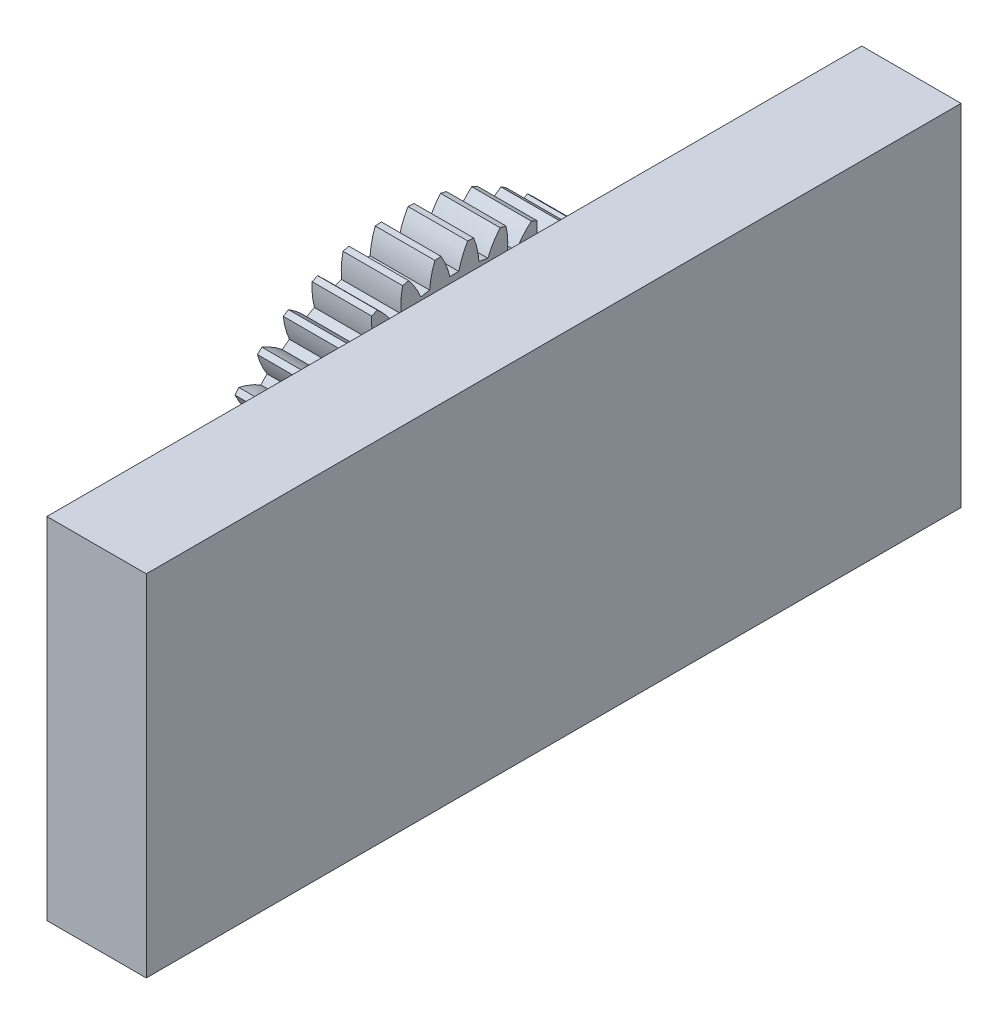
SolidWorks part; units mm, degrees
ref_plane "Plane1" through (0, 0, 0) normal (0, 0, 1) x (1, 0, 0)
ref_plane "Plane2" through (0, 0, 0) normal (0, 1, 0) x (1, 0, 0)
ref_plane "Plane3" through (0, 0, 0) normal (1, 0, 0) x (0, 0, -1)
other "Configuration Table"
sketch "HoldingSke" plane through (0, 0, 0) normal (0, 1, 0) x (1, 0, 0)
  line L0 (0, 0) -> (0.7771, -0.6293)
  line L1 (-15, 0) -> (100, 0) construction
  line L2 (0, 0) -> (-2.1039, 2.3779)
  line L3 (0, 0) -> (-11.863, 4.5341)
  line L4 (0, 0) -> (6.7114, 5.4348)
  line L5 (0, 0) -> (-46.8476, -17.4728)
  line L6 (0, 0) -> (-4.9738, -3.3558)
  line L7 (-2.1039, 2.3779) -> (8.6586, 51.2059)
  line L8 (-76.2, 54.61) -> (-72.9, 54.61)
  line L9 (-71.009, 38.7566) -> (-53.1078, 45.2721)
  line L10 (-76.2, 71.12) -> (104.1128, 71.12)
  line L11 (0, 0) -> (-6, 0)
  line L12 (-76.2, 101.6) -> (-76.162, 101.6)
  line L13 (24.9733, 27.94) -> (52.9518, 28.4284)
  line L14 (24.9733, 27.94) -> (24.9743, 27.94)
  line L15 (24.9733, 27.94) -> (100.4006, 29.5858)
  line L16 (-63.627, -1) -> (-12.827, -1)
  circle A0 centre (0, 0) radius 11
  circle A1 centre (0, 0) radius 18.249
  circle A2 centre (0, 0) radius 37.5
  circle A3 centre (0, 0) radius 11
  dimension "MHD" = 36.498
  dimension "Hub_dia" = 75
  dimension "Bore" = 22
  dimension "MBD" = 22
  dimension "Num_teeth" = 39
  dimension "Pitch" = 1
  dimension "Overall_len" = 50
  dimension "Show_teeth" = 39
  dimension "Thickness" = 6
  dimension "OAL" = 50.0001
  dimension "T_dim" = 3.3
  dimension "Ap" = 20
  dimension "H" = 19.05
  dimension "Pitch_radius" = 180.3128
  dimension "Width" = 6
  dimension "Backlash" = 0.038
  dimension "Addendum_fac" = 1
  dimension "Dedendum_fac" = 1.25
  dimension "Clearance_fac" = 0.25
  dimension "Dedendum_add" = 0.001
  dimension "Module" = 1
sketch "BasProSke" plane through (0, 0, 0) normal (0, 1, 0) x (1, 0, 0)
  line L0 (-10, 0) -> (60, 0) construction
  line L1 (0, 0) -> (0, 20.5)
  line L2 (0, 0) -> (6, 0)
  line L3 (6, 0) -> (6, 20.5)
  line L4 (6, 20.5) -> (0, 20.5)
  dimension "Thickness" = 6
  dimension "Diameter" = 41
revolve "Base-Revolve" add sketch "BasProSke" angle 360 about L0
sketch "TooCutSke" plane through (0, 0, 0) normal (1, 0, 0) x (0, 0, -1)
  line L1 (0, 0) -> (0, 107) construction
  line L2 (0, 0) -> (-0.8517, 19.4814) construction
  line L3 (0, 0) -> (-3.1361, 38.8471) construction
  line L4 (-0.8517, 19.4814) -> (-1.568, 19.4236) construction
  arc A0 (0.4501, 18.2434) -> (-0.4501, 18.2434) centre (0, 0) ccw
  arc A1 (1.358, 20.4804) -> (-1.358, 20.4804) centre (0, 0) ccw
  circle A2 centre (0, 0) radius 19.5 construction
  circle A3 centre (0, 0) radius 18.324 construction
  arc A4 (-0.4501, 18.2434) -> (-1.358, 20.4804) centre (-8.0443, 16.4638) ccw
  arc A5 (1.358, 20.4804) -> (0.4501, 18.2434) centre (8.0443, 16.4638) ccw
  dimension "Root_dia" = 36.498
  dimension "Overcut_dia" = 41.0508
  dimension "Pitch_dia" = 39
  dimension "Base_dia" = 36.648
  dimension "Flank_rad" = 7.8
  dimension "Half_ang" = 4.615
  dimension "Half_CT" = 0.7187
extrude "ToothCut" cut sketch "TooCutSke" along normal through all
fillet "Breaks" [suppressed] radius 0.02
fillet "RootFillets" [suppressed] radius 0.251
pattern_circular "TeethCuts" count 39 every 9.231 about axis through (-10, 0, 0) along (1, 0, 0) of "ToothCut", "RootFillets", "Breaks"
sketch "HubNeaOneSke" plane through (0, 0, 0) normal (-1, 0, 0) x (0, 0, 1)
  circle A0 centre (0, 0) radius 18.249
  dimension "Diameter" = 36.498
extrude "HubNearOne" [suppressed] add sketch "HubNeaOneSke" along normal blind 44.0001
sketch "HubNeaBotSke" plane through (0, 0, 0) normal (-1, 0, 0) x (0, 0, 1)
  circle A0 centre (0, 0) radius 18.249
  dimension "Diameter" = 36.498
extrude "HubNearBoth" [suppressed] add sketch "HubNeaBotSke" along normal blind 22
ref_plane "FarPln" through (6, 0, 0) normal (1, 0, 0) x (0, 0, -1)
sketch "HubFarSke" plane through (6, 0, 0) normal (1, 0, 0) x (0, 0, -1)
  circle A0 centre (0, 0) radius 18.249
  dimension "Diameter" = 36.498
extrude "HubFar" [suppressed] add sketch "HubFarSke" along normal blind 22
sketch "BorSke" plane through (0, 0, 0) normal (1, 0, 0) x (0, 0, -1)
  circle A0 centre (0, 0) radius 11
  dimension "Diameter" = 22
extrude "Bore" cut sketch "BorSke" along normal mid plane 100.0001
sketch "KeySke" plane through (0, 0, 0) normal (1, 0, 0) x (0, 0, -1)
  line L0 (-4, 0) -> (-4, 14.3)
  line L1 (-4, 14.3) -> (4, 14.3)
  line L2 (4, 14.3) -> (4, 0)
  line L3 (0, 0) -> (0, 34) construction
  line L4 (-4, 0) -> (4, 0)
  dimension "Offset" = 14.3
  dimension "Width" = 8
extrude "Keyway" [suppressed] cut sketch "KeySke" along normal mid plane 100.0001
pattern_circular "Keyway2" [suppressed] count 2 every 90 about axis through (-10, 0, 0) along (1, 0, 0)
sketch "Sketch1" plane through (6, 0, 0) normal (1, 0, 0) x (0, 0, -1)
  line L1 (-41.0054, -17.6156) -> (41.0054, -17.6156)
  line L2 (-41.0054, -17.6156) -> (-41.0054, 17.6156)
  line L3 (-41.0054, 17.6156) -> (41.0054, 17.6156)
  line L4 (41.0054, -17.6156) -> (41.0054, 17.6156)
  line L5 (-41.0054, -17.6156) -> (41.0054, 17.6156) construction
  line L6 (-41.0054, 17.6156) -> (41.0054, -17.6156) construction
  point P0 (0, 0)
extrude "Boss-Extrude1" add sketch "Sketch1" along normal blind 10
equation "' \"Module@HoldingSke\" = 6.35"
equation "' \"Num_teeth@HoldingSke\" = 12"
equation "' \"Ap@HoldingSke\" =  20"
equation "' \"Ap@HoldingSke\" = 20"
equation "' \"Width@HoldingSke\" = 0.5 * 25.4"
equation "' \"Hub_dia@HoldingSke\"= 1 * 25.4"
equation "' \"Hub_dia@HoldingSke\" = 1 * 25.4"
equation "' \"Overall_len@HoldingSke\" = 1.0 * 25.4"
equation "' \"Bore@HoldingSke\" = 0.75 * 25.4"
equation "' \"T_dim@HoldingSke\" = 0.1 * 25.4"
equation "' \"Width@KeySke\" = 0.25 * 25.4"
equation "' \"Show_teeth@HoldingSke\" = 13"
equation "' \"Backlash@HoldingSke\" = 0.009 * 25.4"
equation "' \"Addendum_fac@HoldingSke\" = 1.0"
equation "' \"Dedendum_fac@HoldingSke\" = 1.25"
equation "' \"Dedendum_add@HoldingSke\" = 0.00005 * 25.4"
equation "' \"Clearance_fac@HoldingSke\" = 0.25"
equation "\"Pitch@HoldingSke\" = 1 / \"Module@HoldingSke\""
equation "\"Overcut_dia@TooCutSke\" = (\"Num_teeth@HoldingSke\" + 2 * \"Addendum_fac@HoldingSke\") / \"Pitch@HoldingSke\" + 0.002 * 25.4"
equation "\"Pitch_dia@TooCutSke\" = \"Num_teeth@HoldingSke\" / \"Pitch@HoldingSke\""
equation "\"Base_dia@TooCutSke\" = \"Num_teeth@HoldingSke\" / \"Pitch@HoldingSke\" * cos((\"Ap@HoldingSke\"  * 3.14159265 / 180))"
equation "\"Root_dia@TooCutSke\" = (\"Num_teeth@HoldingSke\" + 2) / \"Pitch@HoldingSke\" - 2 * (\"Addendum_fac@HoldingSke\" + \"Dedendum_fac@HoldingSke\") / \"Pitch@HoldingSke\" - \"Dedendum_add@HoldingSke\" * 2"
equation "\"Half_ang@TooCutSke\" = 180 / \"Num_teeth@HoldingSke\""
equation "\"Half_CT@TooCutSke\" = \"Num_teeth@HoldingSke\" / \"Pitch@HoldingSke\" * sin((3.14159265 / 2 / \"Num_teeth@HoldingSke\")) / 2 - 7 * \"Backlash@HoldingSke\" / 4"
equation "\"Flank_rad@TooCutSke\" = \"Num_teeth@HoldingSke\" / \"Pitch@HoldingSke\" / 5"
equation "\"Radius@RootFillets\" = \"Clearance_fac@HoldingSke\" / \"Pitch@HoldingSke\" + \"Dedendum_add@HoldingSke\""
equation "\"Break_rad@Breaks\" = 0.02 / \"Pitch@HoldingSke\""
equation "\"Thickness@HoldingSke\" = \"Width@HoldingSke\""
equation "\"OAL@HoldingSke\" = \"Thickness@HoldingSke\""
equation "\"MHD@HoldingSke\" = (\"Num_teeth@HoldingSke\" + 2) / \"Pitch@HoldingSke\" - 2 * (\"Addendum_fac@HoldingSke\" + \"Dedendum_fac@HoldingSke\")  / \"Pitch@HoldingSke\" - \"Dedendum_add@HoldingSke\" * 2"
equation "\"MBD@HoldingSke\" = (\"Num_teeth@HoldingSke\" + 2) / \"Pitch@HoldingSke\" - 2 * (\"Addendum_fac@HoldingSke\" + \"Dedendum_fac@HoldingSke\")  / \"Pitch@HoldingSke\" - \"Dedendum_add@HoldingSke\" * 2 - 0.002 * 25.4"
equation "\"MHD@HoldingSke\" = ((sgn( \"MHD@HoldingSke\" - \"Hub_dia@HoldingSke\" )-1)*( \"MHD@HoldingSke\" - \"Hub_dia@HoldingSke\" ))/-2+ \"Hub_dia@HoldingSke\""
equation "\"MBD@HoldingSke\" = ((sgn( \"MBD@HoldingSke\" - \"Bore@HoldingSke\" )-1)*( \"MBD@HoldingSke\" - \"Bore@HoldingSke\" ))/-2+ \"Bore@HoldingSke\""
equation "\"OAL@HoldingSke\" = ((sgn( \"OAL@HoldingSke\" - \"Overall_len@HoldingSke\" )+1)*( \"OAL@HoldingSke\" - \"Overall_len@HoldingSke\" ))/2 + \"Overall_len@HoldingSke\" + 0.000002 * 25.4"
equation "\"Num_teeth@TeethCuts\" = int( \"Show_teeth@HoldingSke\" ) + 1"
equation "\"Num_teeth@TeethCuts\" = ((sgn( \"Num_teeth@TeethCuts\" - \"Num_teeth@HoldingSke\" )-1)*( \"Num_teeth@TeethCuts\" - \"Num_teeth@HoldingSke\" ))/-2+ \"Num_teeth@HoldingSke\""
equation "\"Num_teeth@TeethCuts\" = ((sgn( \"Num_teeth@TeethCuts\" - 2.0)+1)*( \"Num_teeth@TeethCuts\" - 2.0))/2 +2.0"
equation "\"Angle@TeethCuts\" = 360.0 / \"Num_teeth@HoldingSke\""
equation "\"Diameter@BasProSke\" = (\"Num_teeth@HoldingSke\" + 2 * \"Addendum_fac@HoldingSke\") / \"Pitch@HoldingSke\""
equation "\"Thickness@BasProSke\"  = \"Thickness@HoldingSke\""
equation "' \"Fillet_rad@BasProSke\" =  \"Thickness@HoldingSke\" * 0.05"
equation "' \"Fillet_rad@BasProSke\" = \"Thickness@HoldingSke\" * 0.05"
equation "\"MHD@HoldingSke\" = ((sgn( \"MHD@HoldingSke\" - \"Root_dia@TooCutSke\" )-1)*( \"MHD@HoldingSke\" - \"Root_dia@TooCutSke\" ))/-2+ \"Root_dia@TooCutSke\""
equation "\"Diameter@HubNeaOneSke\" = \"MHD@HoldingSke\""
equation "\"Length@HubNearOne\" = \"OAL@HoldingSke\" - \"Thickness@BasProSke\""
equation "\"Diameter@HubNeaBotSke\" = \"MHD@HoldingSke\""
equation "\"Length@HubNearBoth\" = ( \"OAL@HoldingSke\" - \"Thickness@BasProSke\" ) / 2.0"
equation "\"Thickness@FarPln\" = \"Thickness@BasProSke\""
equation "\"Diameter@HubFarSke\" = \"MHD@HoldingSke\""
equation "\"Length@HubFar\" = ( \"OAL@HoldingSke\" - \"Thickness@BasProSke\" ) / 2.0"
equation "\"Diameter@BorSke\" = \"MBD@HoldingSke\""
equation "\"D1@Bore\" = \"OAL@HoldingSke\" * 2.0"
equation "\"D1@Keyway\" = \"OAL@HoldingSke\" * 2.0"
equation "\"Offset@KeySke\" = \"T_dim@HoldingSke\" + \"MBD@HoldingSke\" / 2.0"
